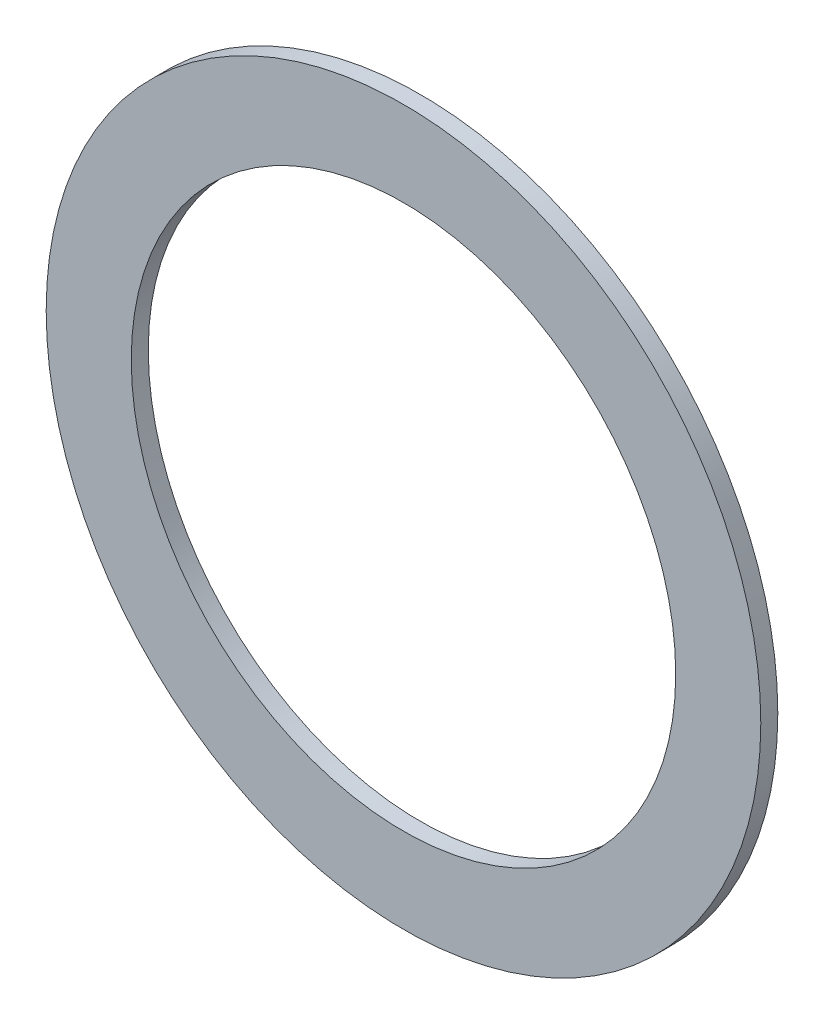
SolidWorks part; units mm, degrees
ref_plane "Plan de face" through (0, 0, 0) normal (0, 0, 1) x (1, 0, 0)
ref_plane "Plan de dessus" through (0, 0, 0) normal (0, 1, 0) x (1, 0, 0)
ref_plane "Plan de droite" through (0, 0, 0) normal (1, 0, 0) x (0, 0, -1)
sketch "Esquisse1" plane through (0, 0, 0) normal (0, 0, 1) x (1, 0, 0)
  circle A0 centre (0, 0) radius 8
  circle A1 centre (0, 0) radius 10.5
  dimension "D1" = 21
  dimension "D2" = 16
extrude "Boss.-Extru.1" add sketch "Esquisse1" along normal blind 0.5
